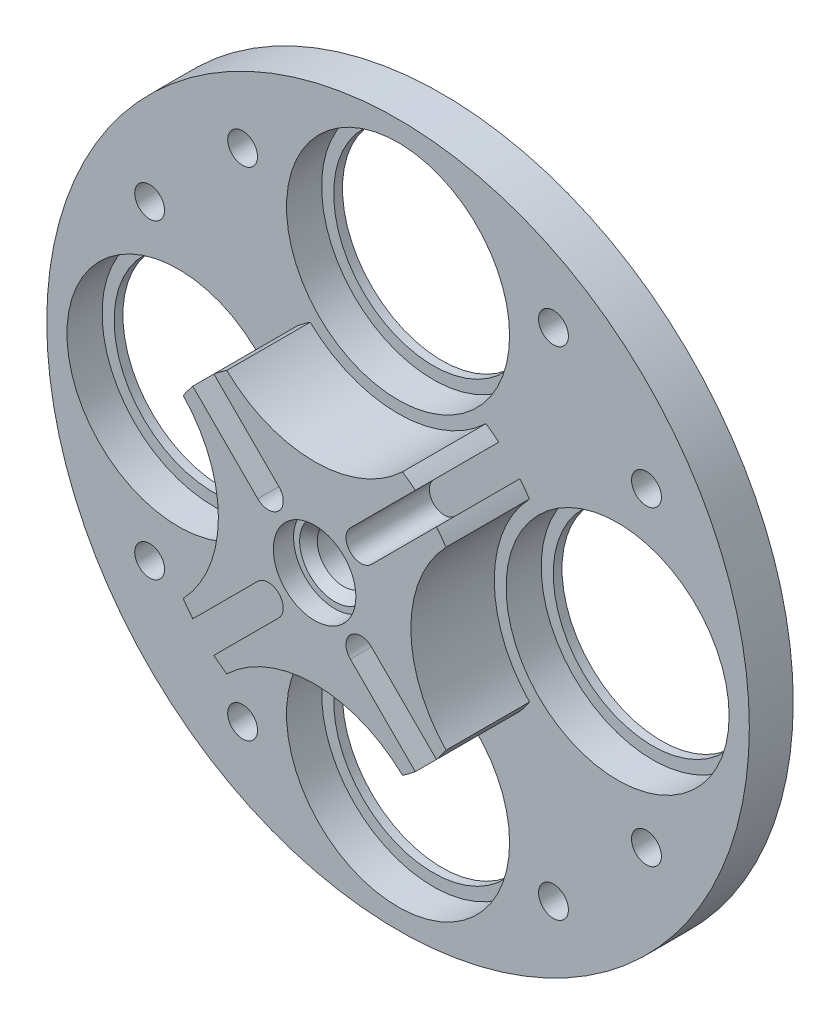
SolidWorks part; units mm, degrees
material "ABS"
ref_plane "Front Plane" through (0, 0, 0) normal (0, 0, 1) x (1, 0, 0)
ref_plane "Top Plane" through (0, 0, 0) normal (0, 1, 0) x (1, 0, 0)
ref_plane "Right Plane" through (0, 0, 0) normal (1, 0, 0) x (0, 0, -1)
sketch "Sketch2" plane through (0, 0, 0) normal (0, 0, 1) x (1, 0, 0)
  line L0 (0, 0) -> (-28.2843, 28.2843) construction
  line L1 (0, 0) -> (-40, 0) construction
  circle A0 centre (0, 0) radius 40
  circle A1 centre (0, 25) radius 11.33
  circle A2 centre (25, 0) radius 11.33
  circle A3 centre (0, -25) radius 11.33
  circle A4 centre (-25, 0) radius 11.33
  circle A5 centre (0, 0) radius 3
  circle A6 centre (17.6978, 28.2843) radius 1.7
  circle A7 centre (-17.6978, 28.2843) radius 1.7
  circle A8 centre (28.2843, -17.6978) radius 1.7
  circle A9 centre (28.2843, 17.6978) radius 1.7
  circle A10 centre (-17.6978, -28.2843) radius 1.7
  circle A11 centre (17.6978, -28.2843) radius 1.7
  circle A12 centre (-28.2843, 17.6978) radius 1.7
  circle A13 centre (-28.2843, -17.6978) radius 1.7
  arc A14 (17.6978, 28.2843) -> (-16.0668, 33.1153) centre (0, 25) cw construction
  point P14 (0, 0)
  point P34 (0, 0)
  dimension "D2" = 22.66
  dimension "D4" = 80
  dimension "D5" = 6
  dimension "D6" = 3.4
  dimension "D8" = 18
  dimension "D3" = 25
  dimension "D7" = 45
  dimension "D1" = 4
  dimension "D10" = 4
extrude "Boss-Extrude1" add sketch "Sketch2" along normal blind 1
sketch "Sketch3" plane through (0, 0, 1) normal (0, 0, 1) x (1, 0, 0)
  circle A0 centre (0, 0) radius 40
  circle A1 centre (0, 25) radius 12.7
  circle A3 centre (25, 0) radius 12.7
  circle A4 centre (0, -25) radius 12.7
  circle A5 centre (-25, 0) radius 12.7
  circle A6 centre (0, 0) radius 40 construction
  circle A7 centre (0, 0) radius 3
  circle A8 centre (0, 0) radius 3 construction
  circle A9 centre (17.6978, 28.2843) radius 1.7
  circle A10 centre (-17.6978, 28.2843) radius 1.7
  circle A11 centre (-17.6978, 28.2843) radius 1.7 construction
  circle A12 centre (17.6978, 28.2843) radius 1.7 construction
  circle A13 centre (28.2843, -17.6978) radius 1.7
  circle A14 centre (28.2843, 17.6978) radius 1.7
  circle A15 centre (-17.6978, -28.2843) radius 1.7
  circle A16 centre (17.6978, -28.2843) radius 1.7
  circle A17 centre (-28.2843, 17.6978) radius 1.7
  circle A18 centre (-28.2843, -17.6978) radius 1.7
  point P17 (0, 0)
  point P45 (0, 0)
  dimension "D1" = 25.4
  dimension "D2" = 4
  dimension "D3" = 4
extrude "Boss-Extrude2" add sketch "Sketch3" along normal blind 4
sketch "Helper lines" plane through (0, 0, 5) normal (0, 0, 1) x (1, 0, 0)
  line L0 (0, 0) -> (12.7279, 12.7279) construction
  line L1 (12.7279, 12.7279) -> (25.4558, 0) construction
  line L2 (0, 0) -> (25.4558, 0) construction
  line L3 (12.2329, 14.6371) -> (4.07, 6.4742) construction
  line L4 (5.2721, 5.2721) -> (4.07, 6.4742) construction
  line L5 (14.6371, 12.2329) -> (6.4742, 4.07) construction
  line L6 (12.2329, 14.6371) -> (14.6371, 12.2329) construction
  line L7 (10.9558, 0) -> (10.9558, 14.5) construction
  circle A0 centre (25.4558, 0) radius 14.5 construction
  circle A1 centre (0, 0) radius 18 construction
  circle A2 centre (25.4558, 0) radius 18 construction
  arc A3 (4.07, 6.4742) -> (6.4742, 4.07) centre (5.2721, 5.2721) ccw construction
  circle A4 centre (0, 0) radius 7.4558 construction
  arc A5 (10.9645, -0.4999) -> (25.9558, 14.4914) centre (10.9558, 14.5) ccw construction
  point P12 (7.4558, 0)
  point P14 (10.9558, 0)
  dimension "D2" = 29
  dimension "D5" = 1
  dimension "D1" = 18
  dimension "D3" = 45
  dimension "D4" = 1.7
  dimension "D6" = 0.5
sketch "Sketch4" plane through (0, 0, 5) normal (0, 0, 1) x (1, 0, 0)
  line L0 (11.4689, 13.8731) -> (4.07, 6.4742)
  line L2 (0, 0) -> (13.435, 13.435) construction
  line L3 (12.2329, 14.6371) -> (14.6371, 12.2329) construction
  line L4 (13.8731, 11.4689) -> (6.4742, 4.07)
  line L5 (12.2329, 14.6371) -> (4.07, 6.4742) construction
  line L6 (14.6371, 12.2329) -> (6.4742, 4.07) construction
  line L7 (13.8731, -11.4689) -> (6.4742, -4.07)
  line L8 (11.4689, -13.8731) -> (4.07, -6.4742)
  line L9 (-11.4689, -13.8731) -> (-4.07, -6.4742)
  line L10 (-13.8731, -11.4689) -> (-6.4742, -4.07)
  line L11 (-13.8731, 11.4689) -> (-6.4742, 4.07)
  line L12 (-11.4689, 13.8731) -> (-4.07, 6.4742)
  arc A0 (11.4689, 13.8731) -> (10.0067, 14.9622) centre (0, 0) ccw
  circle A1 centre (0, 0) radius 18 construction
  arc A2 (4.07, 6.4742) -> (6.4742, 4.07) centre (5.2721, 5.2721) ccw
  arc A3 (14.9622, 10.0067) -> (14.9622, -10.0067) centre (25.4558, 0) ccw
  circle A4 centre (25.4558, 0) radius 14.5 construction
  arc A5 (14.9622, 10.0067) -> (13.8731, 11.4689) centre (0, 0) ccw
  arc A6 (6.4742, -4.07) -> (4.07, -6.4742) centre (5.2721, -5.2721) ccw
  arc A7 (10.0067, -14.9622) -> (-10.0067, -14.9622) centre (0, -25.4558) ccw
  arc A8 (-4.07, -6.4742) -> (-6.4742, -4.07) centre (-5.2721, -5.2721) ccw
  arc A9 (-14.9622, -10.0067) -> (-14.9622, 10.0067) centre (-25.4558, 0) ccw
  arc A10 (-6.4742, 4.07) -> (-4.07, 6.4742) centre (-5.2721, 5.2721) ccw
  arc A11 (-10.0067, 14.9622) -> (10.0067, 14.9622) centre (0, 25.4558) ccw
  arc A12 (-10.0067, 14.9622) -> (-11.4689, 13.8731) centre (0, 0) ccw
  arc A13 (-13.8731, 11.4689) -> (-14.9622, 10.0067) centre (0, 0) ccw
  arc A14 (-11.4689, -13.8731) -> (-10.0067, -14.9622) centre (0, 0) ccw
  arc A15 (-14.9622, -10.0067) -> (-13.8731, -11.4689) centre (0, 0) ccw
  arc A16 (10.0067, -14.9622) -> (11.4689, -13.8731) centre (0, 0) ccw
  arc A17 (13.8731, -11.4689) -> (14.9622, -10.0067) centre (0, 0) ccw
  circle A18 centre (0, 0) radius 3
  circle A19 centre (0, 0) radius 3 construction
  point P52 (0, 0)
  dimension "D1" = 4
extrude "Boss-Extrude3" add sketch "Sketch4" along normal blind 9.5
sketch "Sketch6" plane through (0, 0, 14.5) normal (0, 0, 1) x (1, 0, 0)
  circle A0 centre (0, 0) radius 4.7
  dimension "D1" = 9.4
extrude "Cut-Extrude2" cut sketch "Sketch6" against normal blind 2.3
chamfer "Chamfer1" distance 1 angle 45 1 edges at (3, 0, 12.2)
sketch "Sketch5" plane through (0, 0, 0) normal (0, 0, -1) x (-1, 0, 0)
  line L0 (29.9297, 14.8478) -> (31.5752, 17.6978)
  line L1 (-14.8478, 29.9297) -> (-17.6978, 31.5752)
  line L2 (-17.6978, 31.5752) -> (-20.5478, 29.9297)
  line L3 (-20.5478, 29.9297) -> (-20.5478, 26.6388)
  line L4 (-20.5478, 26.6388) -> (-17.6978, 24.9934)
  line L5 (-17.6978, 24.9934) -> (-14.8478, 26.6388)
  line L6 (-14.8478, 26.6388) -> (-14.8478, 29.9297)
  line L7 (20.5478, 26.6388) -> (20.5478, 29.9297)
  line L8 (20.5478, 29.9297) -> (17.6978, 31.5752)
  line L9 (17.6978, 31.5752) -> (14.8478, 29.9297)
  line L10 (14.8478, 29.9297) -> (14.8478, 26.6388)
  line L11 (14.8478, 26.6388) -> (17.6978, 24.9934)
  line L12 (17.6978, 24.9934) -> (20.5478, 26.6388)
  line L13 (31.5752, 17.6978) -> (29.9297, 20.5478)
  line L14 (29.9297, 20.5478) -> (26.6388, 20.5478)
  line L15 (26.6388, 20.5478) -> (24.9934, 17.6978)
  line L16 (24.9934, 17.6978) -> (26.6388, 14.8478)
  line L17 (26.6388, 14.8478) -> (29.9297, 14.8478)
  line L18 (26.6388, -20.5478) -> (29.9297, -20.5478)
  line L19 (29.9297, -20.5478) -> (31.5752, -17.6978)
  line L20 (31.5752, -17.6978) -> (29.9297, -14.8478)
  line L21 (29.9297, -14.8478) -> (26.6388, -14.8478)
  line L22 (26.6388, -14.8478) -> (24.9934, -17.6978)
  line L23 (24.9934, -17.6978) -> (26.6388, -20.5478)
  line L24 (14.8478, -29.9297) -> (17.6978, -31.5752)
  line L25 (17.6978, -31.5752) -> (20.5478, -29.9297)
  line L26 (20.5478, -29.9297) -> (20.5478, -26.6388)
  line L27 (20.5478, -26.6388) -> (17.6978, -24.9934)
  line L28 (17.6978, -24.9934) -> (14.8478, -26.6388)
  line L29 (14.8478, -26.6388) -> (14.8478, -29.9297)
  line L30 (-20.5478, -26.6388) -> (-20.5478, -29.9297)
  line L31 (-20.5478, -29.9297) -> (-17.6978, -31.5752)
  line L32 (-17.6978, -31.5752) -> (-14.8478, -29.9297)
  line L33 (-14.8478, -29.9297) -> (-14.8478, -26.6388)
  line L34 (-14.8478, -26.6388) -> (-17.6978, -24.9934)
  line L35 (-17.6978, -24.9934) -> (-20.5478, -26.6388)
  line L36 (-29.9297, -14.8478) -> (-31.5752, -17.6978)
  line L37 (-31.5752, -17.6978) -> (-29.9297, -20.5478)
  line L38 (-29.9297, -20.5478) -> (-26.6388, -20.5478)
  line L39 (-26.6388, -20.5478) -> (-24.9934, -17.6978)
  line L40 (-24.9934, -17.6978) -> (-26.6388, -14.8478)
  line L41 (-26.6388, -14.8478) -> (-29.9297, -14.8478)
  line L42 (-26.6388, 20.5478) -> (-29.9297, 20.5478)
  line L43 (-29.9297, 20.5478) -> (-31.5752, 17.6978)
  line L44 (-31.5752, 17.6978) -> (-29.9297, 14.8478)
  line L45 (-29.9297, 14.8478) -> (-26.6388, 14.8478)
  line L46 (-26.6388, 14.8478) -> (-24.9934, 17.6978)
  line L47 (-24.9934, 17.6978) -> (-26.6388, 20.5478)
  circle A0 centre (-17.6978, 28.2843) radius 2.85 construction
  circle A1 centre (17.6978, 28.2843) radius 2.85 construction
  point P57 (0, 0)
  dimension "D1" = 5.7
  dimension "D2" = 4
extrude "Cut-Extrude1" cut sketch "Sketch5" against normal blind 2.1
